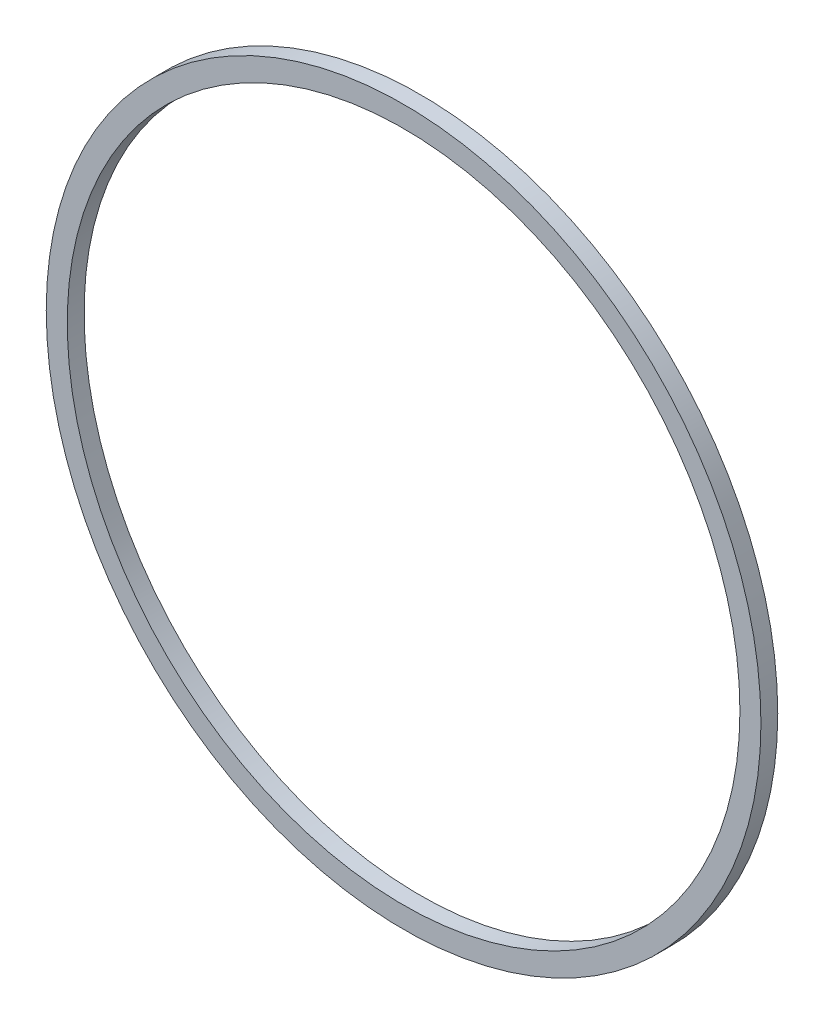
SolidWorks part; units mm, degrees
ref_plane "Front Plane" through (0, 0, 0) normal (0, 0, 1) x (1, 0, 0)
ref_plane "Top Plane" through (0, 0, 0) normal (0, 1, 0) x (1, 0, 0)
ref_plane "Right Plane" through (0, 0, 0) normal (1, 0, 0) x (0, 0, -1)
sketch "Sketch1" plane through (0, 0, 0) normal (0, 0, 1) x (1, 0, 0)
  circle A0 centre (0, 0) radius 40
  circle A1 centre (0, 0) radius 42.5
  dimension "D1" = 80
  dimension "D2" = 85
extrude "Boss-Extrude1" add sketch "Sketch1" along normal blind 2 contours A1 | A0
